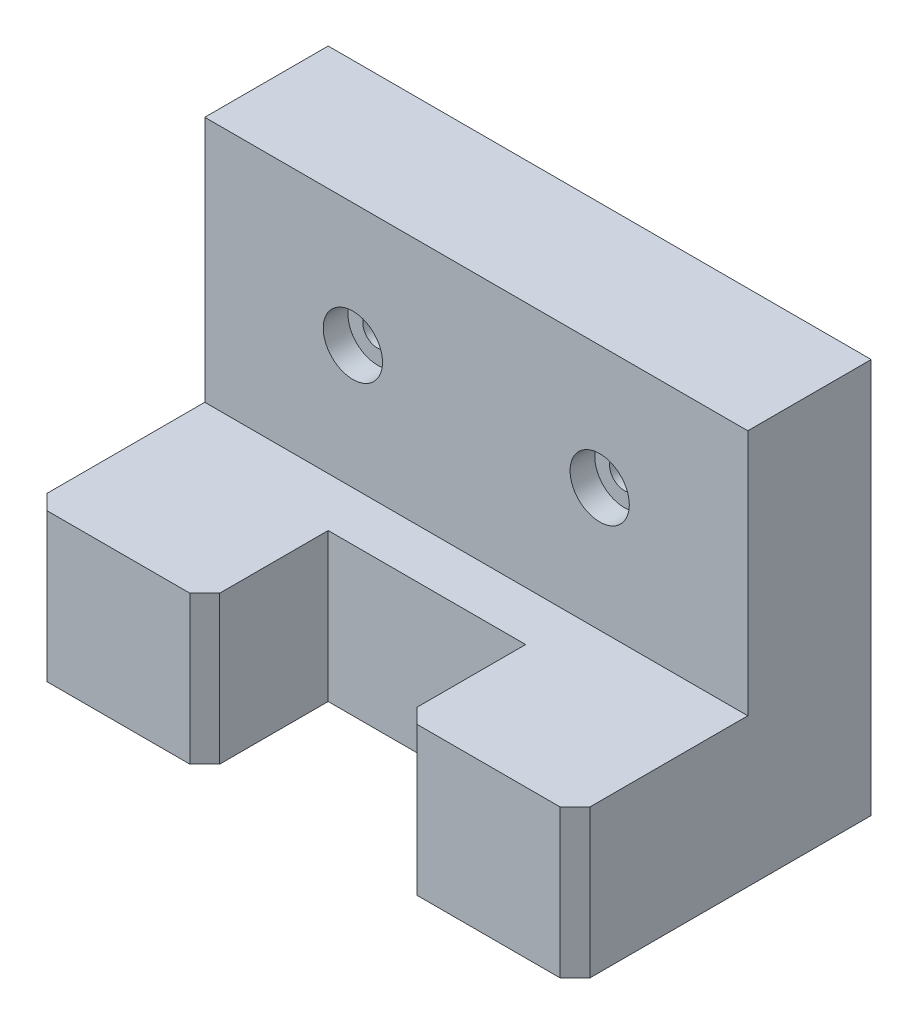
SolidWorks part; units mm, degrees
ref_plane "Front Plane" through (0, 0, 0) normal (0, 0, 1) x (1, 0, 0)
ref_plane "Top Plane" through (0, 0, 0) normal (0, 1, 0) x (1, 0, 0)
ref_plane "Right Plane" through (0, 0, 0) normal (1, 0, 0) x (0, 0, -1)
sketch "Sketch3" plane through (0, 0, 0) normal (1, 0, 0) x (0, 0, -1)
  line L0 (-23.1244, 0) -> (36.8756, 0)
  line L1 (55, 0) -> (-55, 0) construction
  line L2 (36.8756, 0) -> (36.8756, 80)
  line L3 (36.8756, 80) -> (11.8756, 80)
  line L4 (11.8756, 80) -> (11.8756, 30)
  line L5 (11.8756, 30) -> (-23.1244, 30)
  line L6 (-23.1244, 30) -> (-23.1244, 0)
  dimension "D1" = 30
  dimension "D2" = 60
  dimension "D3" = 80
  dimension "D4" = 25
extrude "Boss-Extrude2" add sketch "Sketch3" along normal mid plane 110
sketch "Sketch4" plane through (0, 30, 0) normal (0, 1, 0) x (1, 0, 0)
  line L0 (55, -23.1244) -> (-55, -23.1244) construction
  line L1 (-55, 11.8756) -> (-55, -23.1244) construction
  line L3 (-20, -23.1244) -> (20, -23.1244)
  line L4 (-20, -23.1244) -> (-20, 1.8756)
  line L5 (-20, 1.8756) -> (20, 1.8756)
  line L6 (20, -23.1244) -> (20, 1.8756)
  point P0 (-20, -23.1244)
  point P5 (20, -23.1244)
  dimension "D1" = 35
  dimension "D2" = 40
  dimension "D3" = 25
extrude "Cut-Extrude1" cut sketch "Sketch4" against normal through all
sketch "Sketch5" plane through (0, 0, -11.8756) normal (0, 0, 1) x (1, 0, 0)
  line L0 (-55, 80) -> (-55, 30) construction
  line L1 (55, 80) -> (-55, 80) construction
  circle A0 centre (-25, 55) radius 3
  circle A1 centre (25, 55) radius 3
  point P0 (-25, 55)
  point P1 (25, 55)
  dimension "D4" = 6
  dimension "D5" = 6
  dimension "D1" = 30
  dimension "D2" = 50
  dimension "D3" = 25
extrude "Cut-Extrude2" cut sketch "Sketch5" against normal through all
sketch "Sketch6" plane through (0, 0, -11.8756) normal (0, 0, 1) x (1, 0, 0)
  circle A0 centre (-25, 55) radius 6
  circle A1 centre (25, 55) radius 6
  dimension "D1" = 12
  dimension "D2" = 12
extrude "Cut-Extrude3" cut sketch "Sketch6" against normal blind 5
chamfer "Chamfer1" distance 3 angle 45 4 edges at (55, 15, 23.1244) (20, 15, 23.1244) (-20, 15, 23.1244) (-55, 15, 23.1244)
